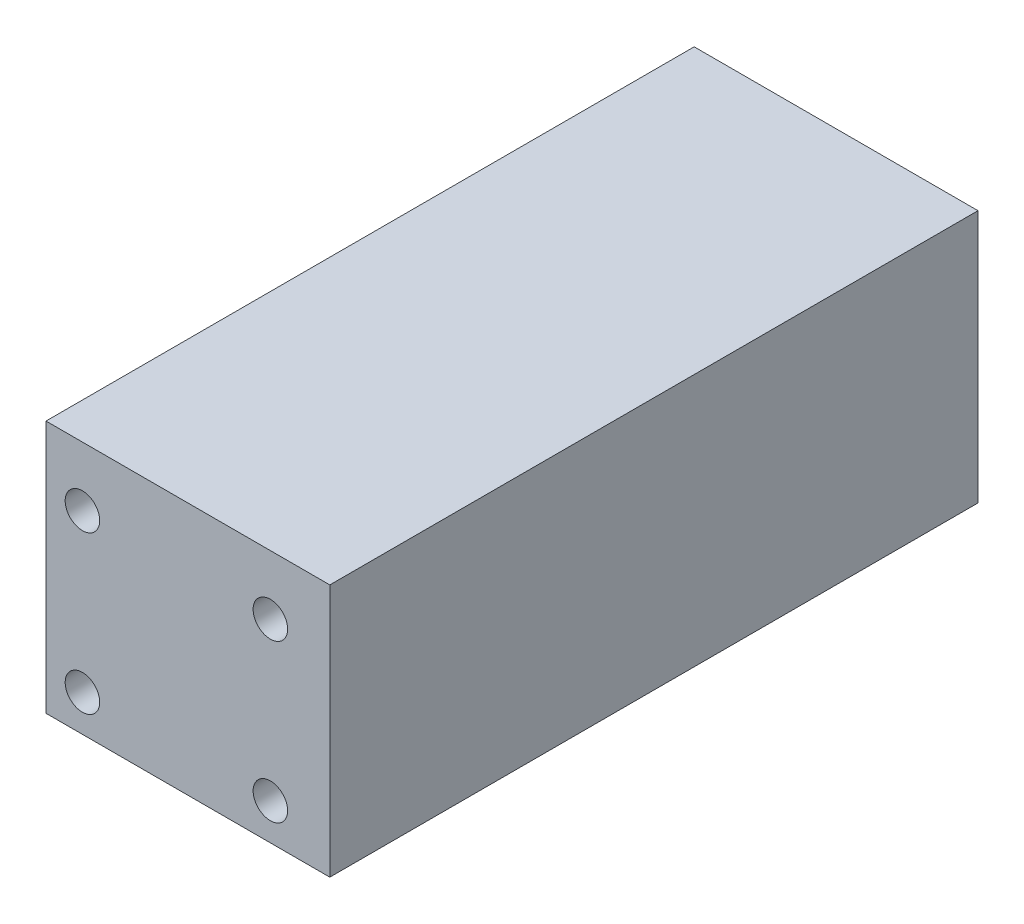
SolidWorks part; units mm, degrees
ref_plane "Front Plane" through (0, 0, 0) normal (0, 0, 1) x (1, 0, 0)
ref_plane "Top Plane" through (0, 0, 0) normal (0, 1, 0) x (1, 0, 0)
ref_plane "Right Plane" through (0, 0, 0) normal (1, 0, 0) x (0, 0, -1)
sketch "Sketch1" plane through (0, 0, 0) normal (0, 0, 1) x (1, 0, 0)
  line L1 (0, 0) -> (34, 0)
  line L2 (0, 0) -> (0, 30)
  line L3 (0, 30) -> (34, 30)
  line L4 (34, 0) -> (34, 30)
  circle A0 centre (4.75, 25.25) radius 2.25
  circle A1 centre (29.25, 25.25) radius 2.25
  circle A2 centre (29.25, 4.75) radius 2.25
  circle A3 centre (4.75, 4.75) radius 2.25
  dimension "D3" = 4.5
  dimension "D6" = 4.5
  dimension "D13" = 4.5
  dimension "D14" = 4.5
  dimension "D1" = 30
  dimension "D2" = 34
  dimension "D4" = 4.75
  dimension "D5" = 4.75
  dimension "D7" = 4.75
  dimension "D8" = 4.75
  dimension "D9" = 4.75
  dimension "D10" = 4.75
  dimension "D11" = 4.75
  dimension "D12" = 4.75
extrude "Boss-Extrude1" add sketch "Sketch1" along normal blind 5
sketch "Sketch2" plane through (0, 0, 0) normal (-1, 0, 0) x (0, 0, 1)
  line L1 (0, 30) -> (5, 30)
  line L2 (0, 30) -> (0, 0)
  line L3 (0, 0) -> (5, 0)
  line L4 (5, 30) -> (5, 0)
extrude "Boss-Extrude2" add sketch "Sketch2" along normal blind 15
sketch "Sketch3" plane through (0, 0, 5) normal (0, 0, 1) x (1, 0, 0)
  line L1 (0, 0) -> (-15, 0)
  line L2 (0, 0) -> (0, 30)
  line L3 (0, 30) -> (-15, 30)
  line L4 (-15, 0) -> (-15, 30)
sketch "Sketch4" plane through (0, 0, 5) normal (0, 0, 1) x (1, 0, 0)
  line L0 (0, 30) -> (-15, 30) construction
  line L1 (-15, 0) -> (-10, 0)
  line L2 (-15, 0) -> (-15, 30)
  line L3 (-15, 30) -> (-10, 30)
  line L4 (-10, 0) -> (-10, 30)
  dimension "D1" = 5
extrude "Boss-Extrude3" add sketch "Sketch4" along normal blind 25
sketch "Sketch5" plane through (-10, 0, 0) normal (1, 0, 0) x (0, 0, -1)
  line L1 (-30, 30) -> (-5, 30) construction
  line L2 (-30, 0) -> (-30, 30) construction
  circle A0 centre (-24, 15) radius 2.5
  circle A1 centre (-10, 15) radius 2.5
  dimension "D1" = 5
  dimension "D2" = 5
  dimension "D3" = 15
  dimension "D4" = 15
  dimension "D5" = 6
  dimension "D6" = 14
extrude "Cut-Extrude1" cut sketch "Sketch5" against normal blind 25
sketch "Sketch6" plane through (0, 30, 0) normal (0, 1, 0) x (1, 0, 0)
  line L1 (-15, -30) -> (0, -30)
  line L2 (-15, -30) -> (-15, 0)
  line L3 (-15, 0) -> (0, 0)
  line L4 (0, -30) -> (0, 0)
extrude "Cut-Extrude2" cut sketch "Sketch6" against normal blind 66
sketch "Sketch7" plane through (0, 0, 5) normal (0, 0, 1) x (1, 0, 0)
  line L1 (0, 30) -> (34, 30)
  line L2 (0, 30) -> (0, 0)
  line L3 (0, 0) -> (34, 0)
  line L4 (34, 30) -> (34, 0)
  circle A0 centre (4.75, 25.25) radius 2.25
  circle A1 centre (29.25, 25.25) radius 2.25
  circle A2 centre (29.25, 4.75) radius 2.25
  circle A3 centre (4.75, 4.75) radius 2.25
extrude "Boss-Extrude4" add sketch "Sketch7" along normal blind 79.5
sketch "Sketch8" plane through (0, 30, 0) normal (0, 1, 0) x (1, 0, 0)
  line L0 (0, -5) -> (-15, -5) construction
  line L1 (0, -5) -> (34, -5)
  line L2 (0, -5) -> (0, -79.5)
  line L3 (0, -79.5) -> (34, -79.5)
  line L4 (34, -5) -> (34, -79.5)
  line L5 (0, -5) -> (-15, -5) construction
  line L6 (34, -84.5) -> (34, 0) construction
  line L8 (34, -84.5) -> (0, -84.5) construction
  dimension "D1" = 5
extrude "Cut-Extrude3" cut sketch "Sketch8" against normal blind 30
sketch "Sketch11" plane through (0, 0, 0) normal (0, 0, -1) x (-1, 0, 0)
  line L0 (0, 30) -> (0, 33)
  line L1 (0, 33) -> (-37, 33)
  line L2 (-37, 33) -> (-37, 0)
  line L3 (-37, 0) -> (-34, 0)
  line L4 (-34, 30) -> (0, 30) construction
  line L5 (-34, 0) -> (-34, 30) construction
  line L6 (-34, 0) -> (-34, 30)
  line L7 (-34, 30) -> (0, 30)
  dimension "D1" = 3
  dimension "D2" = 3
extrude "Boss-Extrude6" add sketch "Sketch11" against normal up to surface (84.5 mm away) up to face at (31.5, 4.75, 84.5)
